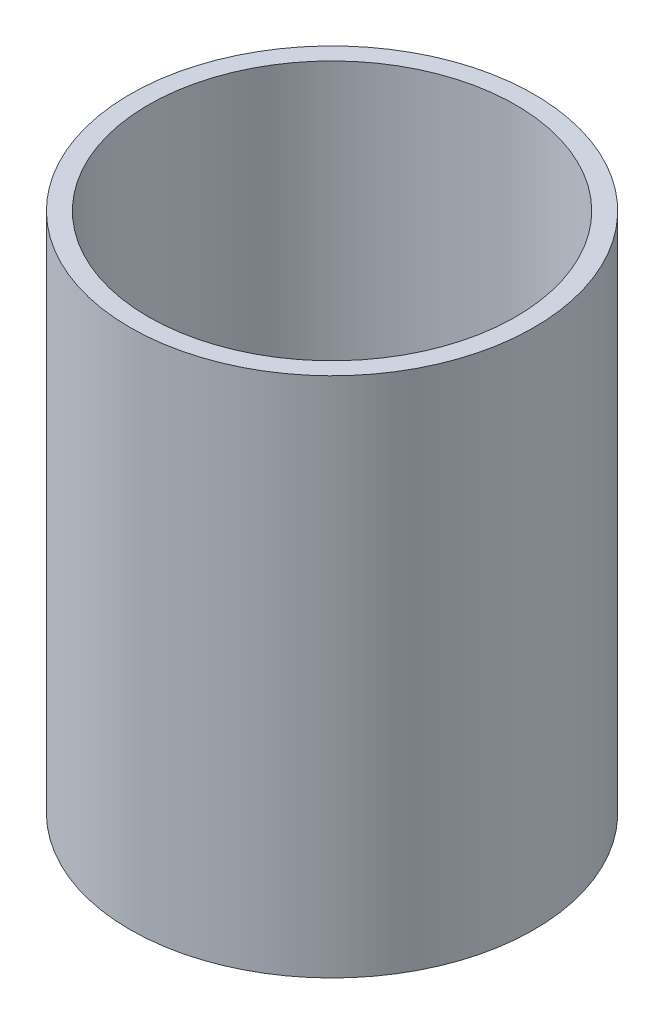
SolidWorks part; units mm, degrees
ref_plane "Front Plane" through (0, 0, 0) normal (0, 0, 1) x (1, 0, 0)
ref_plane "Top Plane" through (0, 0, 0) normal (0, 1, 0) x (1, 0, 0)
ref_plane "Right Plane" through (0, 0, 0) normal (1, 0, 0) x (0, 0, -1)
sketch "Sketch1" plane through (0, 0, 0) normal (0, 1, 0) x (1, 0, 0)
  circle A0 centre (0, 0) radius 27.5
  circle A1 centre (0, 0) radius 25
  dimension "D1" = 55
  dimension "D2" = 50
extrude "Boss-Extrude1" add sketch "Sketch1" along normal blind 71
